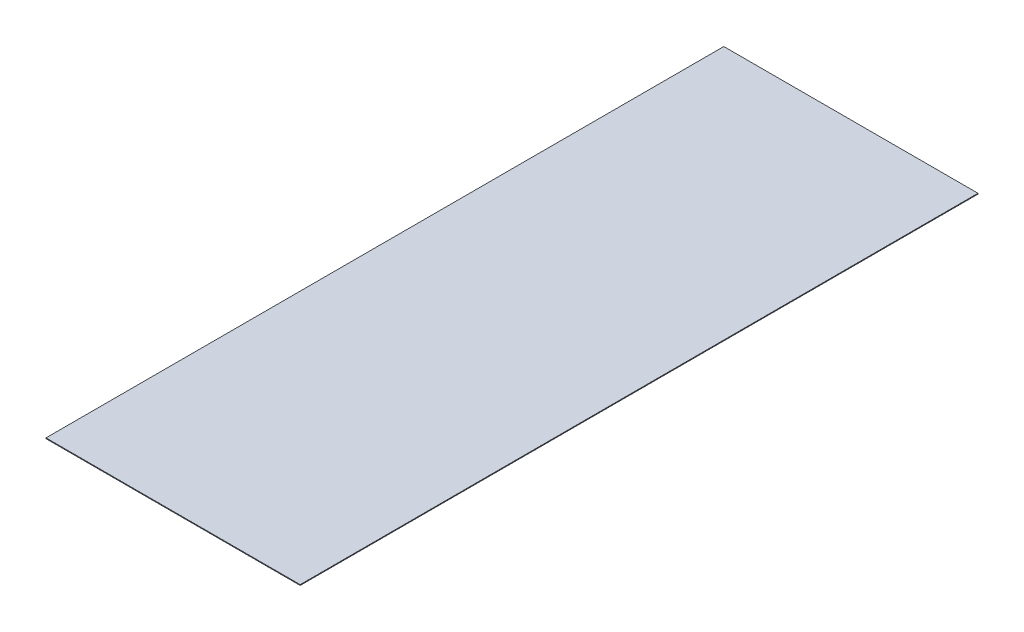
SolidWorks part; units mm, degrees
material "ASTM A36 Acero"
ref_plane "Alzado" through (0, 0, 0) normal (0, 0, 1) x (1, 0, 0)
ref_plane "Planta" through (0, 0, 0) normal (0, 1, 0) x (1, 0, 0)
ref_plane "Vista lateral" through (0, 0, 0) normal (1, 0, 0) x (0, 0, -1)
sketch "Croquis1" plane through (0, 0, 0) normal (0, 1, 0) x (1, 0, 0)
  line L1 (-457.2, -1219.2) -> (457.2, -1219.2)
  line L2 (-457.2, -1219.2) -> (-457.2, 1219.2)
  line L3 (-457.2, 1219.2) -> (457.2, 1219.2)
  line L4 (457.2, -1219.2) -> (457.2, 1219.2)
  line L5 (-457.2, -1219.2) -> (457.2, 1219.2) construction
  line L6 (-457.2, 1219.2) -> (457.2, -1219.2) construction
  point P0 (0, 0)
  dimension "D1" = 2438.4
  dimension "D2" = 914.4
extrude "Saliente-Extruir1" add sketch "Croquis1" along normal blind 2.7
